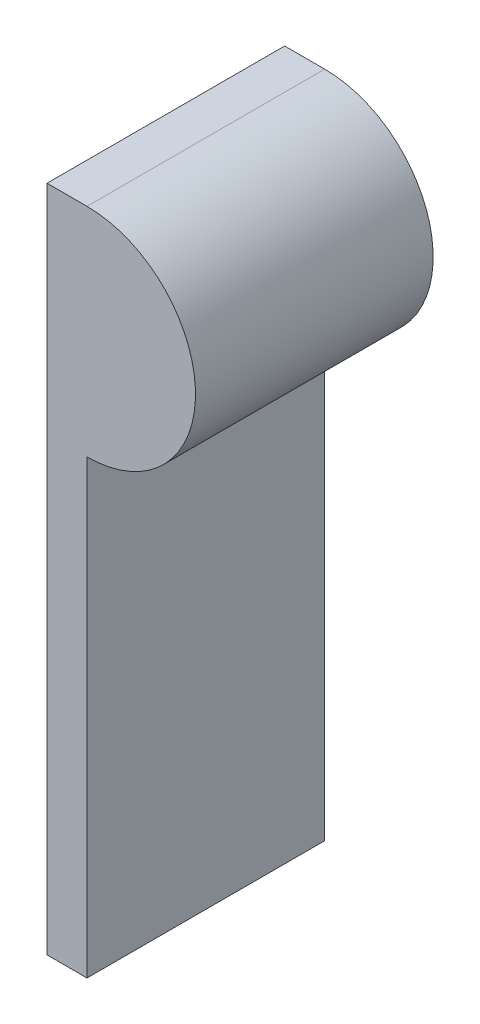
SolidWorks part; units mm, degrees
ref_plane "前视基准面" through (0, 0, 0) normal (0, 0, 1) x (1, 0, 0)
ref_plane "上视基准面" through (0, 0, 0) normal (0, 1, 0) x (1, 0, 0)
ref_plane "右视基准面" through (0, 0, 0) normal (1, 0, 0) x (0, 0, -1)
sketch "草图2" plane through (0, 0, 0) normal (0, 0, 1) x (1, 0, 0)
  line L0 (0, 0.8691) -> (0, 28.9867)
  line L1 (0, 28.9867) -> (1.6836, 28.9867)
  line L2 (1.6836, 19.8582) -> (1.6836, 0.8691)
  line L3 (1.6836, 0.8691) -> (0, 0.8691)
  arc A0 (1.6836, 28.9867) -> (1.6836, 19.8582) centre (1.6836, 24.4224) cw
extrude "凸台-拉伸1" add sketch "草图2" along normal blind 10
